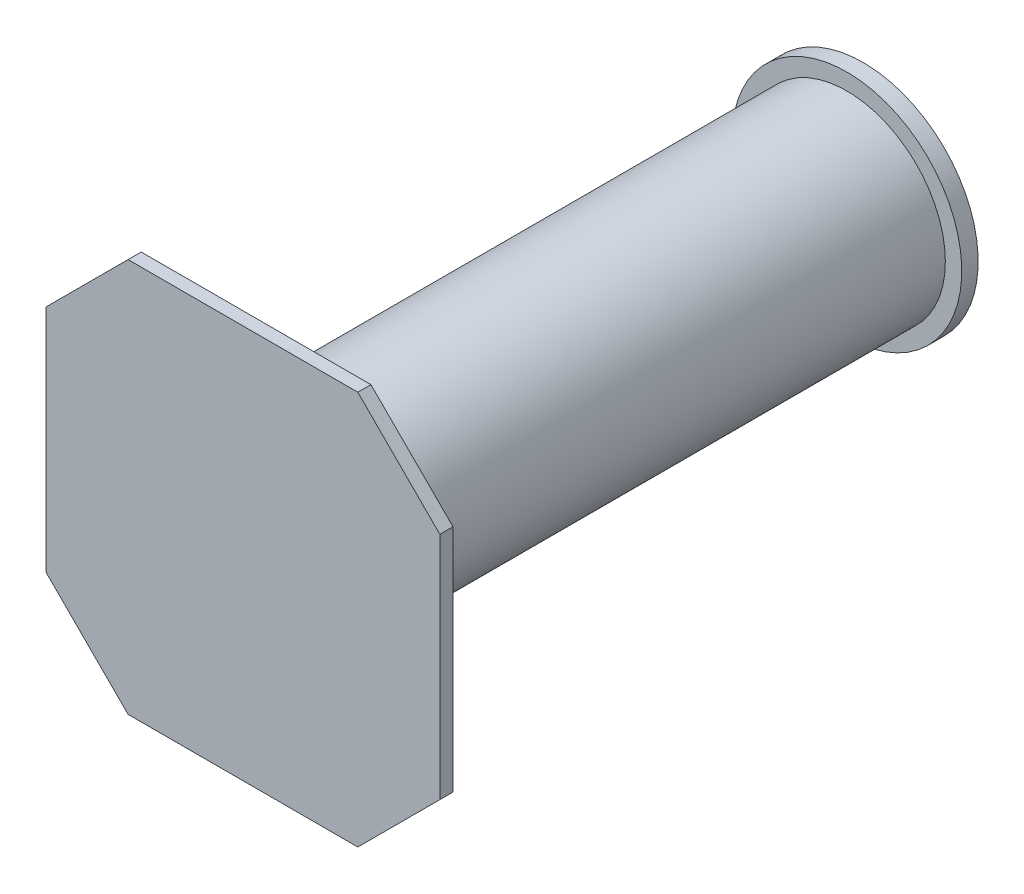
SolidWorks part; units mm, degrees
ref_plane "Front Plane" through (0, 0, 0) normal (0, 0, 1) x (1, 0, 0)
ref_plane "Top Plane" through (0, 0, 0) normal (0, 1, 0) x (1, 0, 0)
ref_plane "Right Plane" through (0, 0, 0) normal (1, 0, 0) x (0, 0, -1)
sketch "Sketch2" plane through (0, 0, 0) normal (0, 0, 1) x (1, 0, 0)
  circle A0 centre (0, 0) radius 60
  dimension "D1" = 120
extrude "Boss-Extrude1" add sketch "Sketch2" along normal blind 360
sketch "Sketch3" plane through (0, 0, 0) normal (0, 0, -1) x (-1, 0, 0)
  circle A1 centre (0, 0) radius 70
  dimension "D1" = 140
extrude "Boss-Extrude2" add sketch "Sketch3" along normal blind 10
sketch "Sketch4" plane through (0, 0, 360) normal (0, 0, 1) x (1, 0, 0)
  line L0 (-70, 120) -> (-120, 70)
  line L1 (70, 120) -> (-70, 120)
  line L2 (120, 70) -> (120, -70)
  line L3 (70, -120) -> (-70, -120)
  line L4 (-120, 70) -> (-120, -70)
  line L5 (120, 120) -> (-120, -120) construction
  line L6 (120, -120) -> (-120, 120) construction
  line L7 (-70, -120) -> (-120, -70)
  line L8 (120, 70) -> (70, 120)
  line L9 (120, -70) -> (70, -120)
  point P4 (0, 0)
  dimension "D1" = 240
  dimension "D2" = 240
extrude "Boss-Extrude4" add sketch "Sketch4" along normal blind 8
sketch "Sketch5" plane through (0, 0, 368) normal (0, 0, 1) x (1, 0, 0)
  line L5 (-47.3957, -95) -> (-45.866, -95)
  circle A0 centre (-39.1457, 95) radius 8.25
  circle A1 centre (-39.1457, -95) radius 8.25
  circle A2 centre (49.0204, 95) radius 8.25
  circle A3 centre (49.0204, -95) radius 8.25
  dimension "D2" = 16.5
  dimension "D3" = 16.5
  dimension "D4" = 16.5
  dimension "D5" = 16.5
